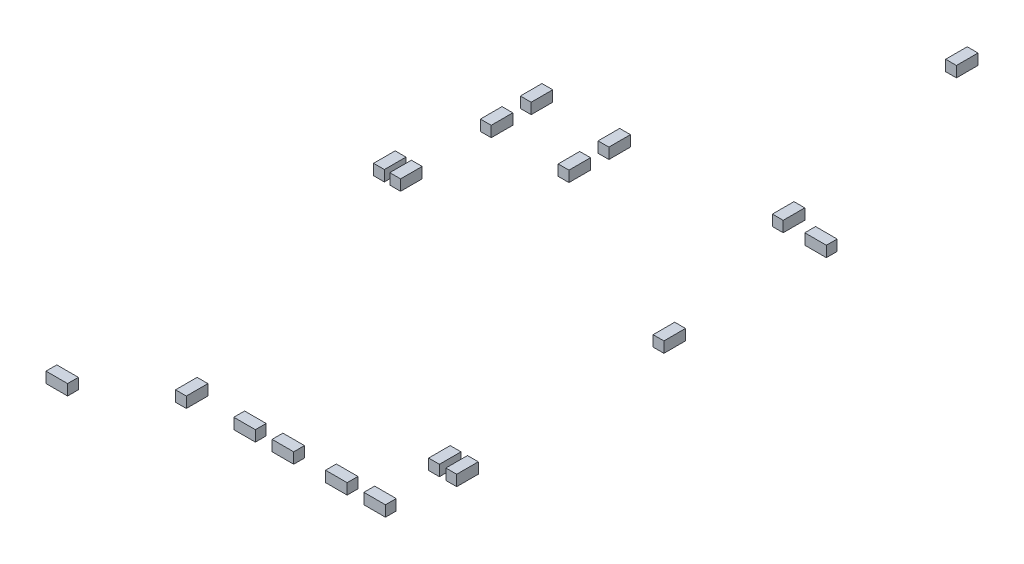
SolidWorks part; units mm, degrees
ref_plane "Front Plane" through (0, 0, 0) normal (0, 0, 1) x (1, 0, 0)
ref_plane "Top Plane" through (0, 0, 0) normal (0, 1, 0) x (1, 0, 0)
ref_plane "Right Plane" through (0, 0, 0) normal (1, 0, 0) x (0, 0, -1)
sketch "Sketch1" plane through (0, 0, 0) normal (0, 1, 0) x (1, 0, 0)
  line L0 (-10.16, -22.8605) -> (-8.89, -25.4) construction
  line L1 (-10.16, 25.4) -> (10.16, 25.4) construction
  line L2 (-10.16, 25.4) -> (-10.16, -25.4) construction
  line L3 (-10.16, -25.4) -> (10.16, -25.4) construction
  line L4 (10.16, 25.4) -> (10.16, -25.4) construction
  line L6 (10.16, -22.8605) -> (8.89, -25.4) construction
  point P4 (0, 25.4)
  point P6 (-10.16, 0)
  dimension "D1" = 20.32
  dimension "D2" = 50.8
  dimension "D3" = 26.57
  dimension "D4" = 1.27
sketch "Sketch2" plane through (0, 0, 0) normal (0, 1, 0) x (1, 0, 0)
  line L0 (0.762, -8.763) -> (1.5494, -8.763) construction
  line L1 (6.8834, -8.255) -> (5.8674, -8.255)
  line L2 (6.8834, -8.255) -> (6.8834, -8.763)
  line L3 (6.8834, -8.763) -> (5.8674, -8.763)
  line L4 (5.8674, -8.255) -> (5.8674, -8.763)
  line L5 (5.08, -8.255) -> (4.064, -8.255)
  line L6 (5.08, -8.255) -> (5.08, -8.763)
  line L7 (5.08, -8.763) -> (4.064, -8.763)
  line L8 (4.064, -8.255) -> (4.064, -8.763)
  line L9 (2.5654, -8.255) -> (1.5494, -8.255)
  line L10 (2.5654, -8.255) -> (2.5654, -8.763)
  line L11 (2.5654, -8.763) -> (1.5494, -8.763)
  line L12 (1.5494, -8.255) -> (1.5494, -8.763)
  line L13 (0.762, -8.255) -> (-0.254, -8.255)
  line L14 (0.762, -8.255) -> (0.762, -8.763)
  line L15 (0.762, -8.763) -> (-0.254, -8.763)
  line L16 (-0.254, -8.255) -> (-0.254, -8.763)
  line L17 (2.5654, -8.763) -> (4.064, -8.763) construction
  line L18 (5.08, -8.763) -> (5.8674, -8.763) construction
  line L19 (10.16, 25.4) -> (10.16, -25.4) construction
  line L20 (-10.16, -25.4) -> (10.16, -25.4) construction
  line L21 (-10.16, 25.4) -> (-10.16, -25.4) construction
  line L22 (-2.2352, -8.001) -> (-2.7432, -8.001)
  line L23 (-2.2352, -8.001) -> (-2.2352, -9.017)
  line L24 (-2.2352, -9.017) -> (-2.7432, -9.017)
  line L25 (-2.7432, -8.001) -> (-2.7432, -9.017)
  line L26 (-5.5372, -10.795) -> (-6.5532, -10.795)
  line L27 (-5.5372, -10.795) -> (-5.5372, -11.303)
  line L28 (-5.5372, -11.303) -> (-6.5532, -11.303)
  line L29 (-6.5532, -10.795) -> (-6.5532, -11.303)
  line L30 (-10.16, 25.4) -> (10.16, 25.4) construction
  line L31 (5.9944, -4.826) -> (6.5024, -4.826)
  line L32 (5.9944, -4.826) -> (5.9944, -5.842)
  line L33 (5.9944, -5.842) -> (6.5024, -5.842)
  line L34 (6.5024, -4.826) -> (6.5024, -5.842)
  line L35 (6.8072, -4.826) -> (7.3152, -4.826)
  line L36 (6.8072, -4.826) -> (6.8072, -5.842)
  line L37 (6.8072, -5.842) -> (7.3152, -5.842)
  line L38 (7.3152, -4.826) -> (7.3152, -5.842)
  line L39 (6.2484, 5.4864) -> (6.7564, 5.4864)
  line L40 (6.2484, 5.4864) -> (6.2484, 4.4704)
  line L41 (6.2484, 4.4704) -> (6.7564, 4.4704)
  line L42 (6.7564, 5.4864) -> (6.7564, 4.4704)
  line L43 (-6.0452, 5.8928) -> (-6.5532, 5.8928)
  line L44 (-6.0452, 5.8928) -> (-6.0452, 4.8768)
  line L45 (-6.0452, 4.8768) -> (-6.5532, 4.8768)
  line L46 (-6.5532, 5.8928) -> (-6.5532, 4.8768)
  line L47 (-6.8072, 5.8928) -> (-7.3152, 5.8928)
  line L48 (-6.8072, 5.8928) -> (-6.8072, 4.8768)
  line L49 (-6.8072, 4.8768) -> (-7.3152, 4.8768)
  line L50 (-7.3152, 5.8928) -> (-7.3152, 4.8768)
  line L51 (-6.604, 10.2108) -> (-6.096, 10.2108)
  line L52 (-6.604, 10.2108) -> (-6.604, 9.1948)
  line L53 (-6.604, 9.1948) -> (-6.096, 9.1948)
  line L54 (-6.096, 10.2108) -> (-6.096, 9.1948)
  line L55 (-6.604, 12.0904) -> (-6.096, 12.0904)
  line L56 (-6.604, 12.0904) -> (-6.604, 11.0744)
  line L57 (-6.604, 11.0744) -> (-6.096, 11.0744)
  line L58 (-6.096, 12.0904) -> (-6.096, 11.0744)
  line L59 (-2.4384, 12.0904) -> (-2.9464, 12.0904)
  line L60 (-2.4384, 12.0904) -> (-2.4384, 11.0744)
  line L61 (-2.4384, 11.0744) -> (-2.9464, 11.0744)
  line L62 (-2.9464, 12.0904) -> (-2.9464, 11.0744)
  line L63 (-2.4384, 10.2108) -> (-2.9464, 10.2108)
  line L64 (-2.4384, 10.2108) -> (-2.4384, 9.1948)
  line L65 (-2.4384, 9.1948) -> (-2.9464, 9.1948)
  line L66 (-2.9464, 10.2108) -> (-2.9464, 9.1948)
  line L68 (6.6802, 12.7) -> (5.6642, 12.7)
  line L69 (6.6802, 12.7) -> (6.6802, 12.192)
  line L70 (6.6802, 12.192) -> (5.6642, 12.192)
  line L71 (5.6642, 12.7) -> (5.6642, 12.192)
  line L72 (4.6482, 12.192) -> (4.1402, 12.192)
  line L73 (4.6482, 12.192) -> (4.6482, 13.208)
  line L74 (4.6482, 13.208) -> (4.1402, 13.208)
  line L75 (4.1402, 12.192) -> (4.1402, 13.208)
  line L76 (1.905, 23.5966) -> (2.413, 23.5966)
  line L77 (1.905, 23.5966) -> (1.905, 22.5806)
  line L78 (1.905, 22.5806) -> (2.413, 22.5806)
  line L79 (2.413, 23.5966) -> (2.413, 22.5806)
  point P28 (-2.2352, -8.509)
  point P29 (-0.254, -8.509)
  dimension "D1" = 1.016
  dimension "D2" = 2.8194
  dimension "D3" = 0.508
  dimension "D4" = 6.096
  dimension "D5" = 10.414
  dimension "D6" = 17.145
  dimension "D7" = 7.9248
  dimension "D8" = 4.6228
  dimension "D9" = 14.605
  dimension "D10" = 3.3528
  dimension "D11" = 4.1656
  dimension "D12" = 4.1148
  dimension "D13" = 3.3528
  dimension "D14" = 2.8956
  dimension "D15" = 7.7216
  dimension "D16" = 4.064
  dimension "D17" = 16.2052
  dimension "D18" = 20.5232
  dimension "D19" = 3.937
  dimension "D20" = 3.9116
  dimension "D21" = 20.9296
  dimension "D22" = 4.4958
  dimension "D23" = 6.0198
  dimension "D24" = 13.208
  dimension "D25" = 2.8194
  dimension "D26" = 8.255
extrude "Boss-Extrude1" add sketch "Sketch2" along normal blind 0.508
